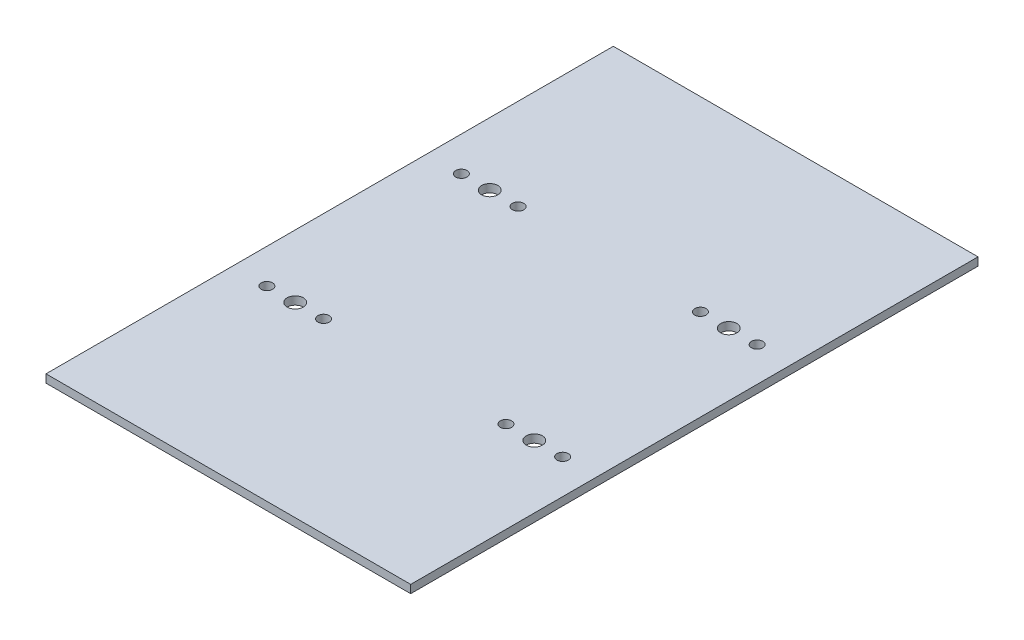
SolidWorks part; units mm, degrees
ref_plane "Front Plane" through (0, 0, 0) normal (0, 0, 1) x (1, 0, 0)
ref_plane "Top Plane" through (0, 0, 0) normal (0, 1, 0) x (1, 0, 0)
ref_plane "Right Plane" through (0, 0, 0) normal (1, 0, 0) x (0, 0, -1)
sketch "Sketch1" plane through (0, 0, 0) normal (0, 1, 0) x (1, 0, 0)
  line L0 (-45, 0) -> (45, 0) construction
  line L1 (-45, -70) -> (45, -70)
  line L2 (-45, -70) -> (-45, 70)
  line L3 (-45, 70) -> (45, 70)
  line L4 (45, -70) -> (45, 70)
  line L5 (-45, -70) -> (45, 70) construction
  line L6 (-45, 70) -> (45, -70) construction
  line L7 (0, 70) -> (0, -70) construction
  line L8 (-45, 24) -> (45, 24) construction
  circle A0 centre (-29.5, 24) radius 2
  circle A1 centre (-36.5, 24) radius 1.4
  circle A2 centre (-22.5, 24) radius 1.4
  circle A3 centre (22.5, 24) radius 1.4
  circle A4 centre (29.5, 24) radius 2
  circle A5 centre (36.5, 24) radius 1.4
  circle A6 centre (36.5, -24) radius 1.4
  circle A7 centre (29.5, -24) radius 2
  circle A8 centre (22.5, -24) radius 1.4
  circle A9 centre (-22.5, -24) radius 1.4
  circle A10 centre (-29.5, -24) radius 2
  circle A11 centre (-36.5, -24) radius 1.4
  point P1 (0, 0)
  dimension "D3" = 2.8
  dimension "D4" = 2.8
  dimension "D5" = 4
  dimension "D1" = 90
  dimension "D2" = 140
  dimension "D6" = 7
  dimension "D7" = 7
  dimension "D8" = 29.5
  dimension "D9" = 24
extrude "Boss-Extrude1" add sketch "Sketch1" along normal blind 2
